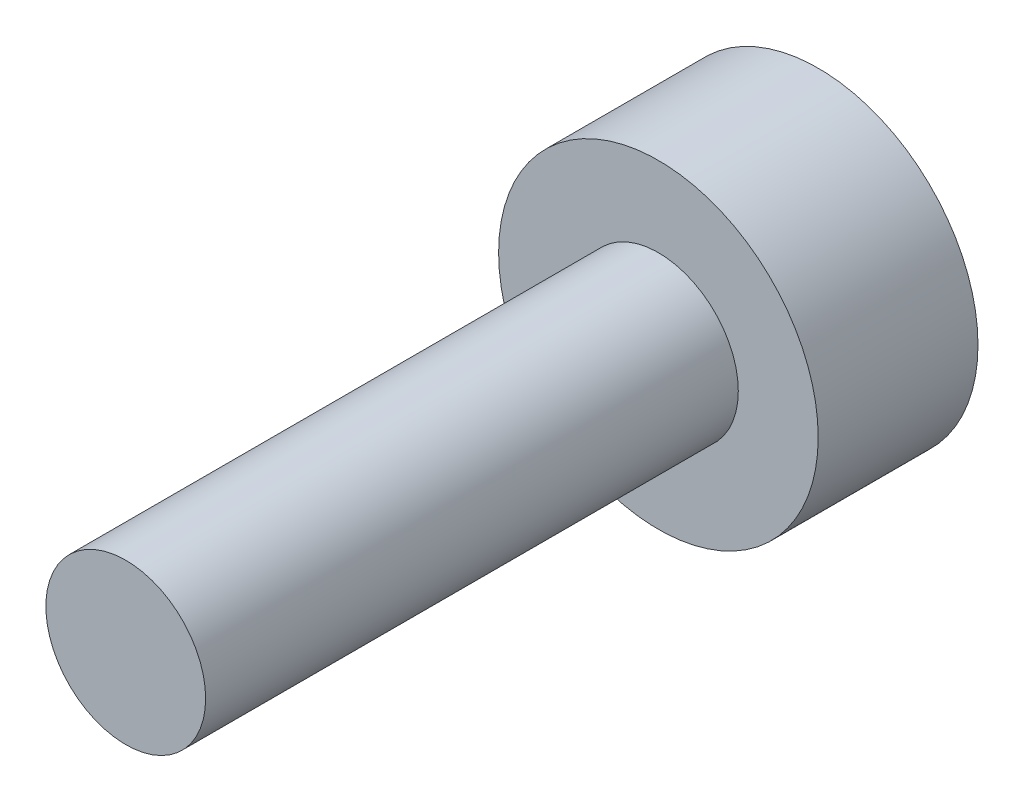
SolidWorks part; units mm, degrees
ref_plane "前视基准面" through (0, 0, 0) normal (0, 0, 1) x (1, 0, 0)
ref_plane "上视基准面" through (0, 0, 0) normal (0, 1, 0) x (1, 0, 0)
ref_plane "右视基准面" through (0, 0, 0) normal (1, 0, 0) x (0, 0, -1)
sketch "草图1" plane through (0, 0, 0) normal (0, 0, 1) x (1, 0, 0)
  circle A0 centre (0, 0) radius 3
  dimension "D1" = 6
extrude "凸台-拉伸1" add sketch "草图1" along normal blind 3
sketch "草图2" plane through (0, 0, 3) normal (0, 0, 1) x (1, 0, 0)
  circle A0 centre (0, 0) radius 1.5
  dimension "D1" = 3
extrude "凸台-拉伸2" add sketch "草图2" along normal blind 10
